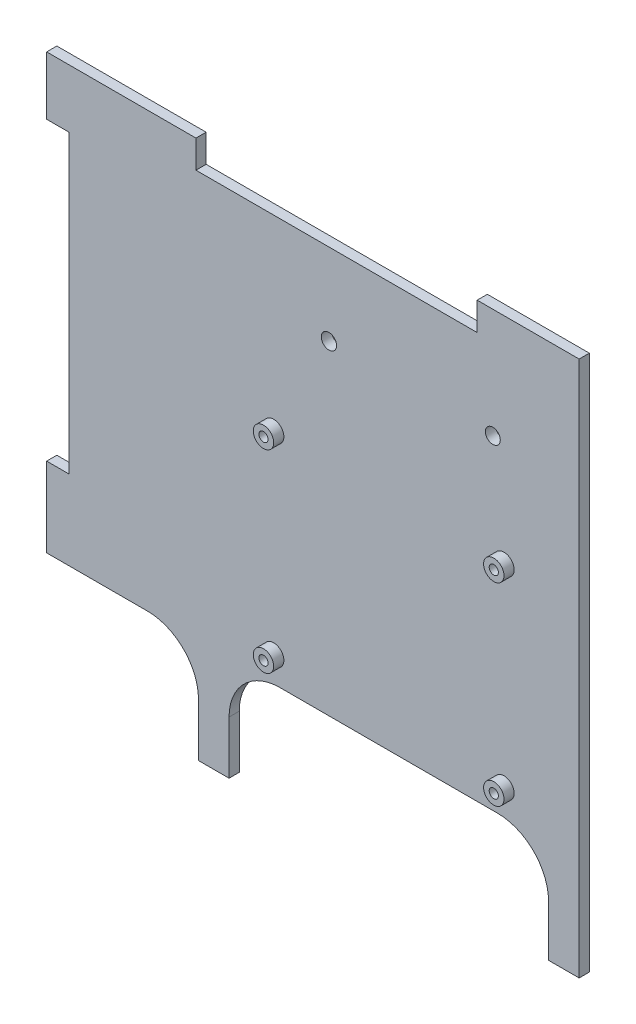
SolidWorks part; units mm, degrees
ref_plane "Front Plane" through (0, 0, 0) normal (0, 0, 1) x (1, 0, 0)
ref_plane "Top Plane" through (0, 0, 0) normal (0, 1, 0) x (1, 0, 0)
ref_plane "Right Plane" through (0, 0, 0) normal (1, 0, 0) x (0, 0, -1)
sketch "Sketch2" plane through (0, 0, 0) normal (0, 0, 1) x (1, 0, 0)
  line L0 (-114.427, 27.9324) -> (-120.015, 27.9324)
  line L1 (12.7083, -33.147) -> (12.7083, -91.059)
  line L2 (-120.015, -81.1224) -> (-120.015, 59.2464) construction
  line L3 (-120.015, 27.9324) -> (-120.015, 42.4834)
  line L4 (-120.015, 42.4834) -> (-82.8068, 42.4834)
  line L7 (-114.427, -45.847) -> (-120.015, -45.847)
  line L9 (25.4, -91.059) -> (-25.4, -91.059) construction
  line L10 (-120.015, -45.847) -> (-120.015, -65.659)
  line L13 (-110.729, -85.725) -> (110.74, -85.725) construction
  line L23 (12.7083, 42.5458) -> (12.7083, -33.147)
  line L24 (12.7083, 42.5458) -> (-12.7139, 42.5442)
  line L25 (-12.7139, 42.5442) -> (-12.7083, 35.5524)
  line L26 (-82.8012, 35.5524) -> (-82.8068, 42.4834)
  line L30 (-114.427, 35.5524) -> (-114.427, -81.9186) construction
  line L31 (-82.8012, 35.5524) -> (-12.7083, 35.5524)
  line L32 (-114.427, 27.9324) -> (-114.427, -45.847)
  line L33 (-107.569, -91.567) -> (-82.169, -91.567) construction
  line L34 (-107.569, -91.567) -> (-25.4, -91.567) construction
  line L35 (-82.169, -91.567) -> (-74.549, -91.567)
  line L36 (-74.549, -91.567) -> (-74.549, -85.725)
  line L37 (-82.169, -91.567) -> (-82.169, -85.725)
  line L38 (-82.169, -85.725) -> (-82.169, -78.359)
  line L39 (-74.549, -85.725) -> (-74.549, -78.359)
  line L44 (12.7083, -91.059) -> (5.0883, -91.059)
  line L45 (5.0883, -91.059) -> (5.0883, -78.359)
  line L46 (-7.6117, -65.659) -> (-61.849, -65.659)
  line L47 (-120.015, -65.659) -> (-94.869, -65.659)
  arc A1 (-82.169, -78.359) -> (-94.869, -65.659) centre (-94.869, -78.359) ccw
  arc A2 (-74.549, -78.359) -> (-61.849, -65.659) centre (-61.849, -78.359) cw
  arc A5 (5.0883, -78.359) -> (-7.6117, -65.659) centre (-7.6117, -78.359) ccw
  point P61 (-74.549, -65.659)
  point P65 (12.7083, -45.847)
  dimension "D1" = 12.7
  dimension "D2" = 12.7
  dimension "D3" = 12.7
  dimension "D4" = 12.7
extrude "Boss-Extrude1" add sketch "Sketch2" along normal blind 2.54
sketch "Sketch3" plane through (0, 0, 2.54) normal (0, 0, 1) x (1, 0, 0)
  line L0 (-34.7304, -65.659) -> (-34.7304, -59.309) construction
  line L1 (-61.849, -65.659) -> (-7.6117, -65.659) construction
  line L2 (-34.7304, -59.309) -> (-7.1714, -59.309) construction
  line L3 (-34.7304, -59.309) -> (-62.2894, -59.309) construction
  line L4 (-62.2894, -59.309) -> (-64.5754, -59.309) construction
  line L5 (-7.1714, -59.309) -> (-4.8854, -59.309) construction
  line L6 (-63.4324, -58.166) -> (-63.4324, -12.192) construction
  line L7 (-6.0284, -58.166) -> (-6.0284, -12.192) construction
  line L8 (-34.7304, -59.309) -> (-34.7304, -1.2761) construction
  line L9 (-6.0284, -35.179) -> (-63.4324, -35.179) construction
  line L10 (-34.7304, -11.049) -> (-7.1714, -11.049) construction
  line L11 (-34.7304, -11.049) -> (-62.2894, -11.049) construction
  circle A0 centre (-6.0284, -59.309) radius 1.143 construction
  circle A1 centre (-63.4324, -59.309) radius 1.143 construction
  circle A2 centre (-6.0284, -11.049) radius 1.143 construction
  circle A3 centre (-63.4324, -11.049) radius 1.143 construction
  circle A4 centre (-63.4324, -59.309) radius 2.54
  circle A5 centre (-6.0284, -59.309) radius 2.54
  circle A6 centre (-6.0284, -11.049) radius 2.54
  circle A7 centre (-63.4324, -11.049) radius 2.54
extrude "Boss-Extrude2" add sketch "Sketch3" along normal blind 2.54
sketch "Sketch4" plane through (0, 0, 5.08) normal (0, 0, 1) x (1, 0, 0)
  circle A1 centre (-6.0284, -59.309) radius 1.143
  circle A2 centre (-63.4324, -59.309) radius 1.143
  circle A3 centre (-63.4324, -11.049) radius 1.143
  circle A4 centre (-6.0284, -11.049) radius 1.143
extrude "Cut-Extrude1" cut sketch "Sketch4" against normal through all
sketch "Sketch5" plane through (0, 0, 2.54) normal (0, 0, 1) x (1, 0, 0)
  line L0 (-47.7547, 35.5524) -> (-47.7547, 15.2093) construction
  line L1 (-12.7083, 35.5524) -> (-82.8012, 35.5524) construction
  line L2 (-47.7547, 15.2093) -> (-10.6707, 15.2093) construction
  line L3 (-10.6707, 15.2093) -> (-6.9531, 15.2093) construction
  line L4 (-47.7547, 15.2093) -> (-51.5672, 15.2093) construction
  circle A0 centre (-8.8119, 15.2093) radius 1.8588
  circle A1 centre (-49.661, 15.2093) radius 1.9062
extrude "Cut-Extrude2" cut sketch "Sketch5" against normal through all
